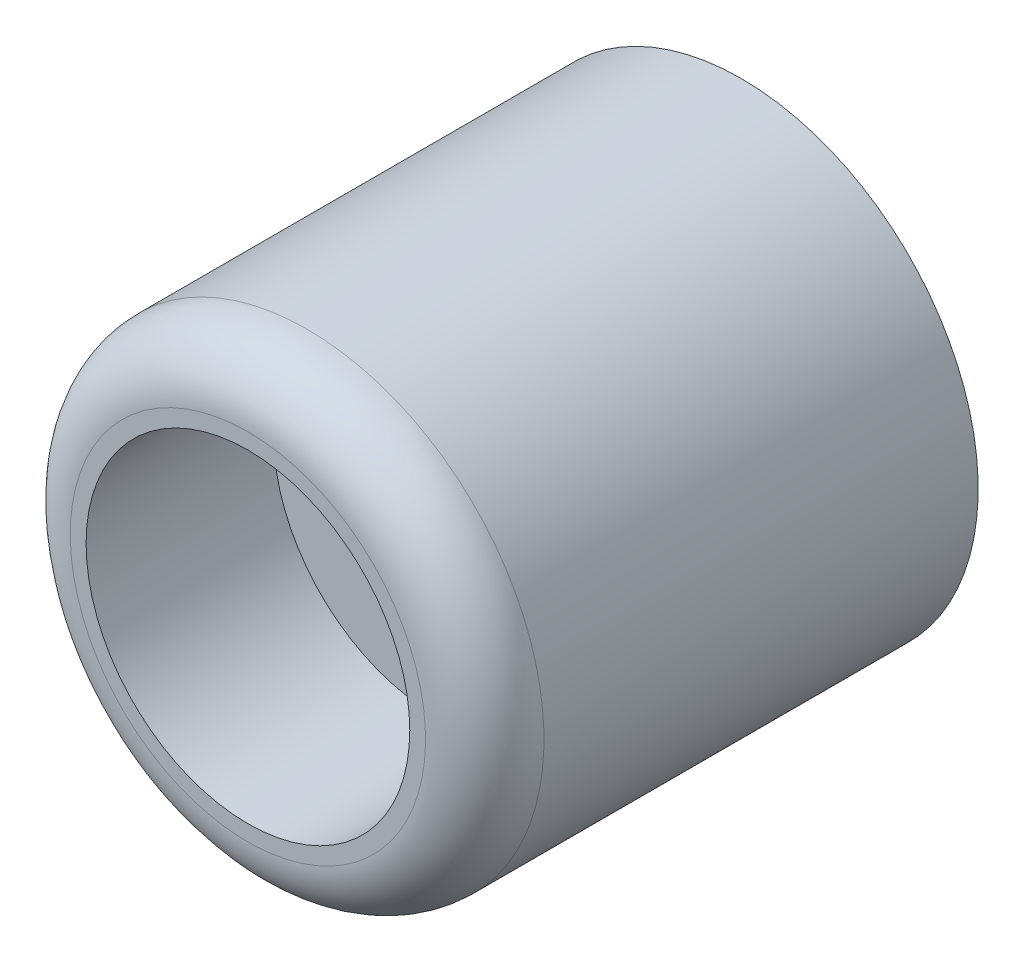
SolidWorks part; units mm, degrees
ref_plane "Front Plane" through (0, 0, 0) normal (0, 0, 1) x (1, 0, 0)
ref_plane "Top Plane" through (0, 0, 0) normal (0, 1, 0) x (1, 0, 0)
ref_plane "Right Plane" through (0, 0, 0) normal (1, 0, 0) x (0, 0, -1)
sketch "Sketch1" plane through (0, 0, 0) normal (1, 0, 0) x (0, 0, -1)
  line L0 (0, 4.7625) -> (0, 6.096)
  line L1 (0, 6.096) -> (-11.176, 6.096)
  line L3 (-12.7, 4.572) -> (-12.7, 4.1656)
  line L4 (-7.874, 2.4257) -> (-7.874, 4.1656)
  line L5 (-7.874, 2.4257) -> (-2.3368, 2.4257)
  line L6 (-2.3368, 2.4257) -> (0, 4.7625)
  line L7 (-7.874, 4.1656) -> (-12.7, 4.1656)
  line L8 (-12.7, 0) -> (-23.876, 0) construction
  arc A0 (-11.176, 6.096) -> (-12.7, 4.572) centre (-11.176, 4.572) ccw
  dimension "D1" = 4.826
  dimension "D3" = 1.524
  dimension "D4" = 4.8514
  dimension "D5" = 8.3312
  dimension "D6" = 45
  dimension "D7" = 12.192
  dimension "D8" = 9.525
  dimension "D9" = 12.7
revolve "Revolve1" add sketch "Sketch1" angle 360 about L8
